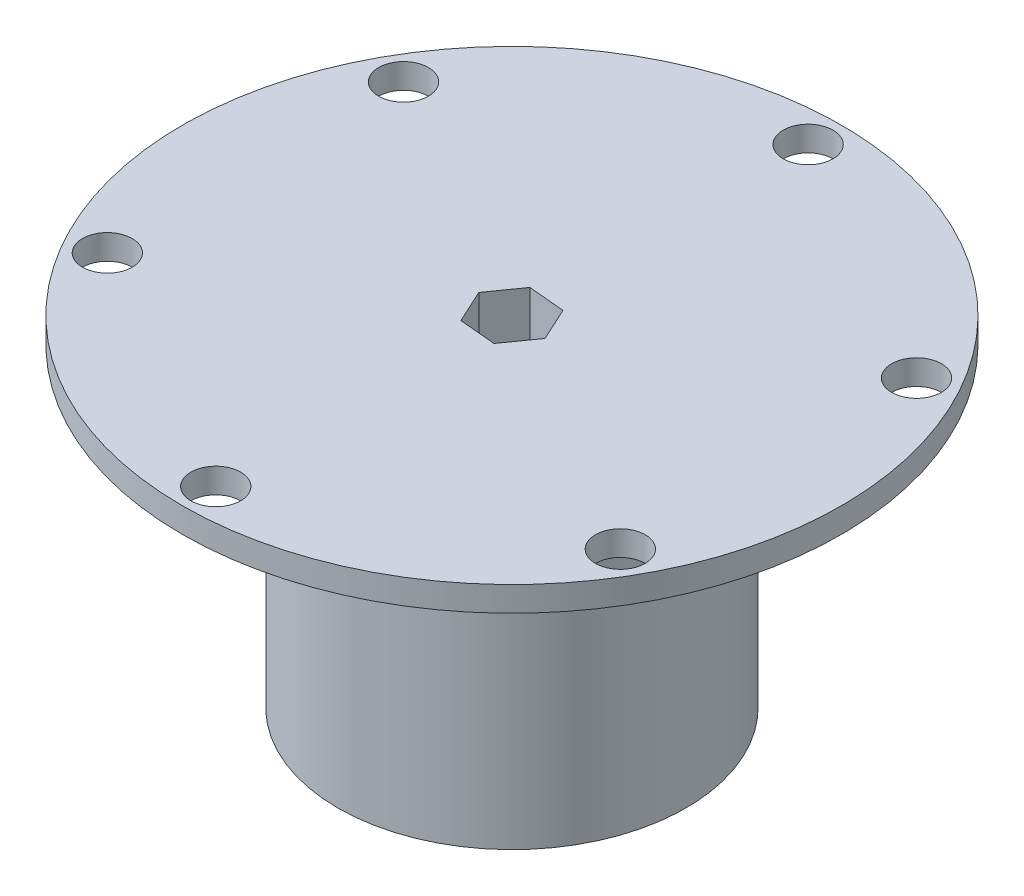
SolidWorks part; units mm, degrees
ref_plane "Front" through (0, 0, 0) normal (0, 0, 1) x (1, 0, 0)
ref_plane "Top" through (0, 0, 0) normal (0, 1, 0) x (1, 0, 0)
ref_plane "Right" through (0, 0, 0) normal (1, 0, 0) x (0, 0, -1)
sketch "Sketch1" plane through (0, 0, 0) normal (0, 1, 0) x (1, 0, 0)
  circle A0 centre (0, 0) radius 14
extrude "Boss-Extrude1" add sketch "Sketch1" along normal blind 25.3
sketch "Sketch2" plane through (0, 25.3, 0) normal (0, 1, 0) x (1, 0, 0)
  circle A0 centre (0, 0) radius 26.5
extrude "Boss-Extrude2" add sketch "Sketch2" along normal blind 2
sketch "Sketch3" plane through (0, 27.3, 0) normal (0, 1, 0) x (1, 0, 0)
  line L1 (1.2345, -2.6732) -> (2.9323, -0.2675)
  line L2 (2.9323, -0.2675) -> (1.6978, 2.4057)
  line L3 (1.6978, 2.4057) -> (-1.2345, 2.6732)
  line L4 (-1.2345, 2.6732) -> (-2.9323, 0.2675)
  line L5 (-2.9323, 0.2675) -> (-1.6978, -2.4057)
  line L6 (-1.6978, -2.4057) -> (1.2345, -2.6732)
  circle A0 centre (0, 0) radius 2.55 construction
  circle A2 centre (0, 23.815) radius 2
  circle A3 centre (20.6244, 11.9075) radius 2
  circle A4 centre (20.6244, -11.9075) radius 2
  circle A5 centre (0, -23.815) radius 2
  circle A6 centre (-20.6244, -11.9075) radius 2
  circle A7 centre (-20.6244, 11.9075) radius 2
  point P24 (0, 0)
  dimension "D2" = 6
  dimension "D1" = 5.1
extrude "Cut-Extrude1" cut sketch "Sketch3" against normal blind 32
